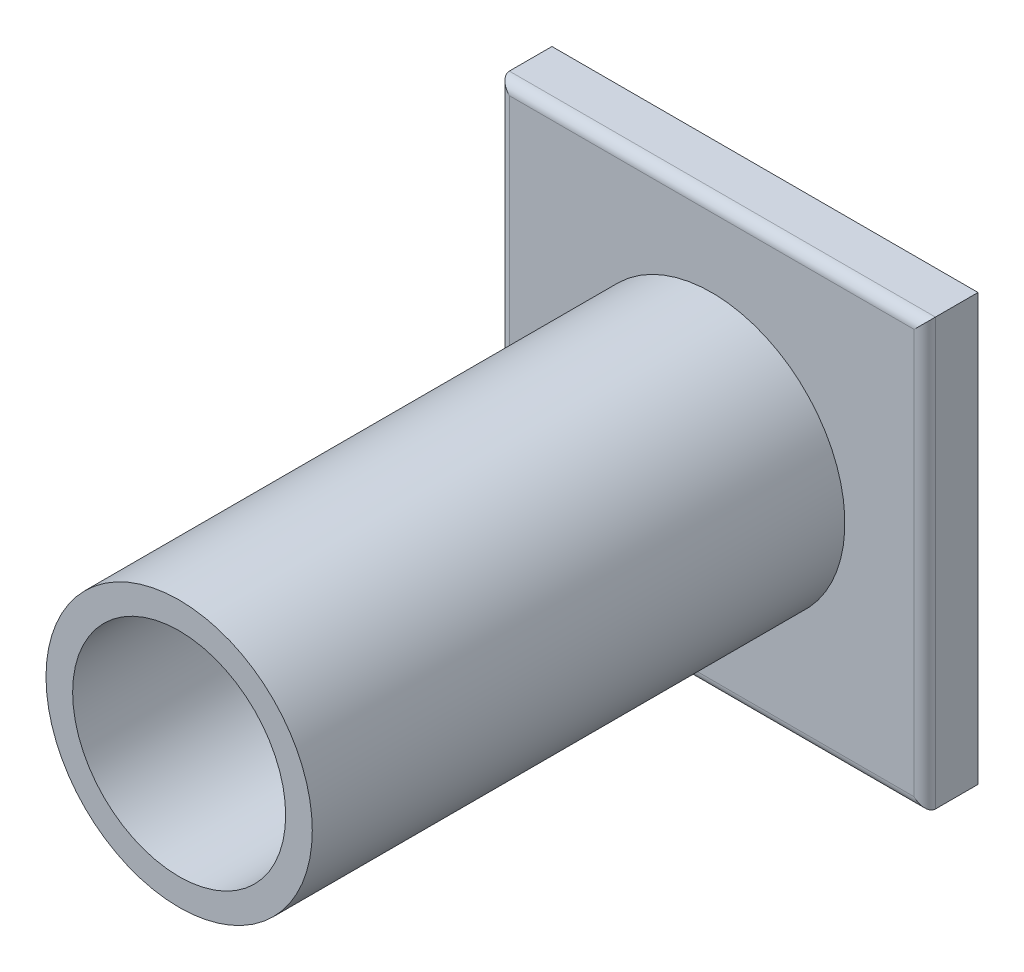
SolidWorks part; units mm, degrees
ref_plane "Front Plane" through (0, 0, 0) normal (0, 0, 1) x (1, 0, 0)
ref_plane "Top Plane" through (0, 0, 0) normal (0, 1, 0) x (1, 0, 0)
ref_plane "Right Plane" through (0, 0, 0) normal (1, 0, 0) x (0, 0, -1)
sketch "Sketch1" plane through (0, 0, 0) normal (0, 0, 1) x (1, 0, 0)
  line L1 (-400, -400) -> (400, -400)
  line L2 (-400, -400) -> (-400, 400)
  line L3 (-400, 400) -> (400, 400)
  line L4 (400, -400) -> (400, 400)
  line L5 (-400, -400) -> (400, 400) construction
  line L6 (-400, 400) -> (400, -400) construction
  point P0 (0, 0)
  dimension "D1" = 800
  dimension "D2" = 800
extrude "Boss-Extrude1" add sketch "Sketch1" along normal blind 100
sketch "Sketch2" plane through (0, 0, 100) normal (0, 0, 1) x (1, 0, 0)
  circle A0 centre (0, 0) radius 200
  circle A1 centre (0, 0) radius 250
  dimension "D1" = 500
  dimension "D2" = 400
extrude "Boss-Extrude2" add sketch "Sketch2" along normal blind 1000
fillet "Fillet1" radius 20 4 edges at (0, 400, 100) (-400, 0, 100) (400, 0, 100) (0, -400, 100)
